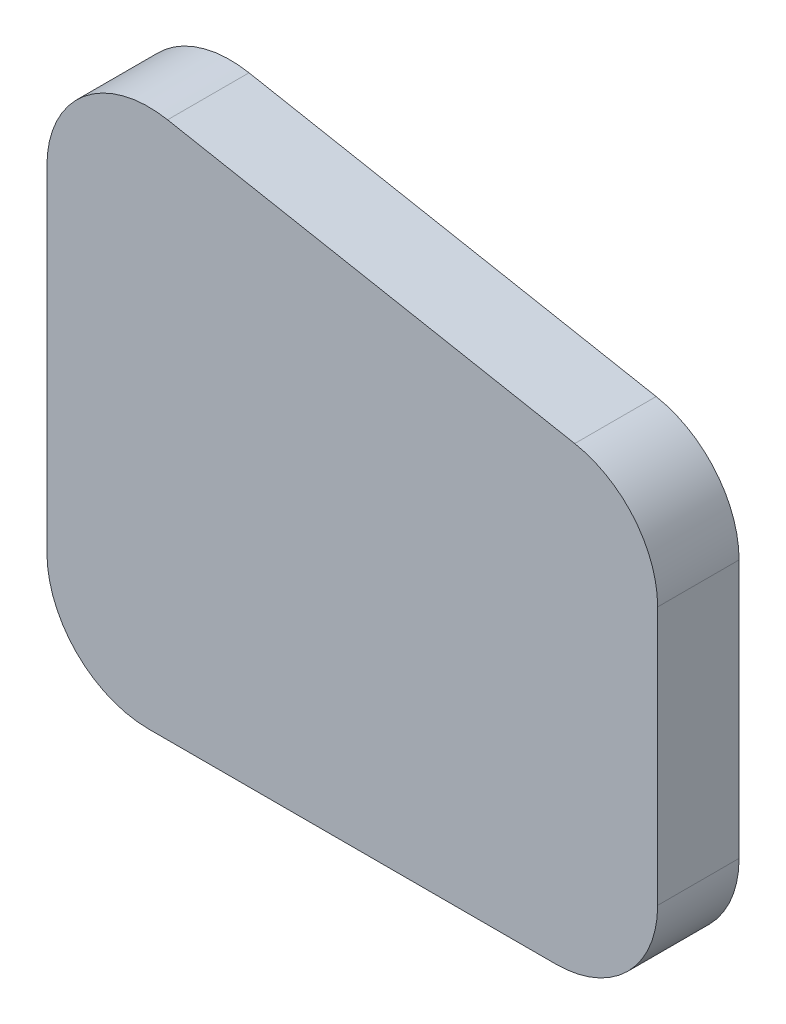
SolidWorks part; units mm, degrees
ref_plane "Front Plane" through (0, 0, 0) normal (0, 0, 1) x (1, 0, 0)
ref_plane "Top Plane" through (0, 0, 0) normal (0, 1, 0) x (1, 0, 0)
ref_plane "Right Plane" through (0, 0, 0) normal (1, 0, 0) x (0, 0, -1)
sketch "Sketch1" plane through (0, 0, 0) normal (0, 0, 1) x (1, 0, 0)
  line L4 (50.7306, -28.1032) -> (63.4306, -28.1032)
  line L5 (66.6056, -24.9282) -> (66.6056, -16.8658)
  line L6 (64.019, -13.7458) -> (51.319, -11.3505)
  line L7 (47.5556, -14.4705) -> (47.5556, -24.9282)
  line L8 (50.7306, -28.1032) -> (63.4306, -28.1032)
  line L9 (66.6056, -24.9282) -> (66.6056, -16.8658)
  line L10 (64.019, -13.7458) -> (51.319, -11.3505)
  line L11 (47.5556, -14.4705) -> (47.5556, -24.9282)
  arc A4 (47.5556, -24.9282) -> (50.7306, -28.1032) centre (50.7306, -24.9282) ccw
  arc A5 (63.4306, -28.1032) -> (66.6056, -24.9282) centre (63.4306, -24.9282) ccw
  arc A6 (66.6056, -16.8658) -> (64.019, -13.7458) centre (63.4306, -16.8658) ccw
  arc A7 (51.319, -11.3505) -> (47.5556, -14.4705) centre (50.7306, -14.4705) ccw
  arc A8 (47.5556, -24.9282) -> (50.7306, -28.1032) centre (50.7306, -24.9282) ccw
  arc A9 (63.4306, -28.1032) -> (66.6056, -24.9282) centre (63.4306, -24.9282) ccw
  arc A10 (66.6056, -16.8658) -> (64.019, -13.7458) centre (63.4306, -16.8658) ccw
  arc A11 (51.319, -11.3505) -> (47.5556, -14.4705) centre (50.7306, -14.4705) ccw
  dimension "D1" = 0
extrude "Boss-Extrude1" add sketch "Sketch1" along normal blind 2.54
